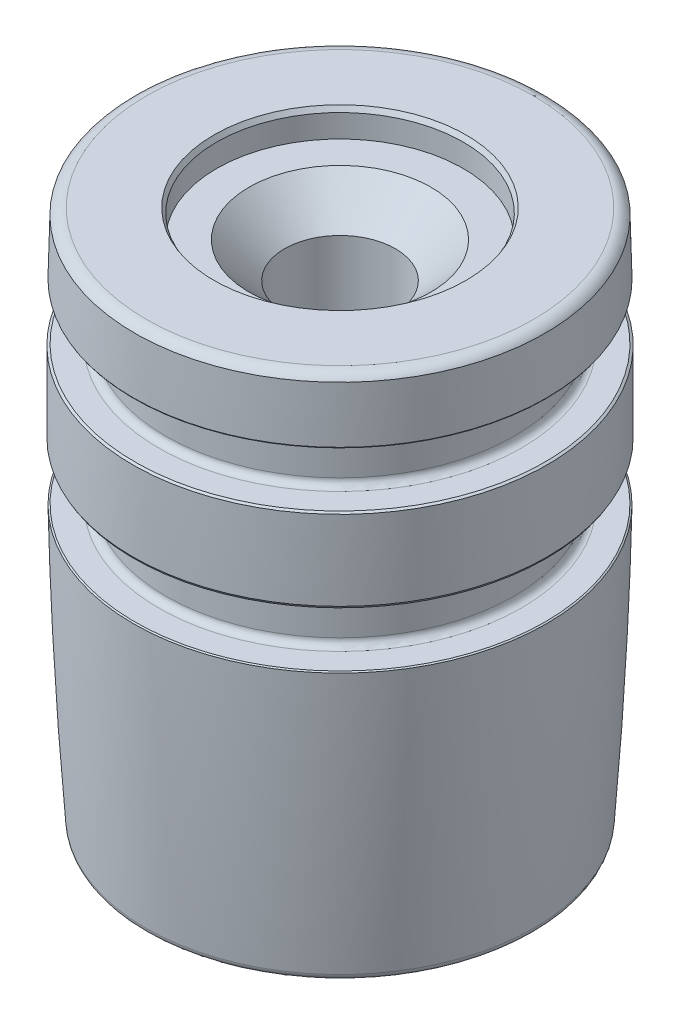
SolidWorks part; units mm, degrees
material "Delrin (POM), Black"
ref_plane "Front Plane" through (0, 0, 0) normal (0, 0, 1) x (1, 0, 0)
ref_plane "Top Plane" through (0, 0, 0) normal (0, 1, 0) x (1, 0, 0)
ref_plane "Right Plane" through (0, 0, 0) normal (1, 0, 0) x (0, 0, -1)
sketch "Sketch1" plane through (0, 0, 0) normal (0, 0, 1) x (1, 0, 0)
  line L0 (-8.9, 0) -> (-14.975, 0)
  line L1 (-14.975, 0) -> (-14.975, -4.5)
  line L2 (-14.975, -4.5) -> (-12.575, -4.5)
  line L3 (-12.575, -4.5) -> (-12.575, -8.5)
  line L4 (-12.575, -8.5) -> (-14.975, -8.5)
  line L5 (-14.975, -8.5) -> (-14.975, -14.5)
  line L6 (-14.975, -14.5) -> (-12.575, -14.5)
  line L7 (-12.575, -14.5) -> (-12.575, -18.5)
  line L8 (-12.575, -18.5) -> (-14.975, -18.5)
  line L9 (-14.975, -18.5) -> (-14.975, -38.5)
  line L10 (-14.975, -38.5) -> (-9.535, -38.5)
  line L11 (-9.535, -38.5) -> (-9.535, -22.5)
  line L12 (-9.535, -22.5) -> (-4, -22.5)
  line L13 (-4, -22.5) -> (-4, -4.5657)
  line L14 (-6.5657, -2) -> (-8.9, -2)
  line L15 (-8.9, -2) -> (-8.9, 0)
  line L16 (0, 0) -> (0, -38.5) construction
  line L17 (-3.9687, -30.5) -> (3.9688, -30.5) construction
  line L18 (-6.5657, -2) -> (-4, -4.5657)
  line L19 (-5.7071, -3.7071) -> (-4.2929, -2.2929) construction
  circle A0 centre (-5, -3) radius 1 construction
  circle A1 centre (-14.075, -6.6315) radius 1.5 construction
  point P19 (0, -30.5)
  point P26 (-5.2828, -3.2828)
  point P28 (-15.575, -6.6315)
  point P29 (-14.075, -6.6315)
  dimension "D11" = 2
  dimension "D17" = 3
  dimension "D1" = 19.07
  dimension "D2" = 16
  dimension "D3" = 29.95
  dimension "D4" = 8
  dimension "D5" = 7.9375
  dimension "D6" = 8
  dimension "D7" = 17.8
  dimension "D8" = 2
  dimension "D9" = 2.4
  dimension "D10" = 4
  dimension "D12" = 0.6
  dimension "D13" = 45
  dimension "D14" = 6
  dimension "D15" = 2.5
  dimension "D16" = 4
  dimension "D18" = 0.6
revolve "Revolve1" add sketch "Sketch1" angle 360 about L16
fillet "Fillet1" radius 1 2 edges at (-14.975, 0, 0) (-14.975, -38.5, 0)
chamfer "Chamfer1" distance 0.2 angle 60 1 edges at (-8.9, 0, 0)
chamfer "Chamfer2" distance 0.1 angle 60 4 edges at (-14.975, -18.5, 0) (-14.975, -14.5, 0) (-14.975, -8.5, 0) (-14.975, -4.5, 0)
fillet "Fillet2" radius 0.5 4 edges at (-12.575, -14.5, 0) (-12.575, -18.5, 0) (-12.575, -4.5, 0) (-12.575, -8.5, 0)
chamfer "Chamfer3" distance 0.4 angle 60 2 edges at (-4, -22.5, 0) (-9.535, -38.5, 0)
sketch "Sketch2" plane through (0, 0, 0) normal (0, 0, 1) x (1, 0, 0)
  line L0 (-14.975, -8.6) -> (-14.975, -14.3268) construction
  line L1 (-13.975, -38.5) -> (13.975, -38.5) construction
  line L2 (-13.7345, 18.6448) -> (-23.701, 18.6448)
  line L3 (-23.701, 18.6448) -> (-23.701, -42.8072)
  line L4 (-23.701, -42.8072) -> (-13.975, -38.5)
  line L5 (0, -0.3464) -> (0, 16.7486) construction
  line L6 (-8.9, -0.3464) -> (8.9, -0.3464) construction
  arc A0 (-13.975, -38.5) -> (-13.7345, 18.6448) centre (351.0139, -11.4634) cw
  point P3 (-14.975, -11.4634)
  dimension "D1" = 1
revolve "Cut-Revolve1" cut sketch "Sketch2" angle 360 about L5
fillet "Fillet3" radius 0.5 1 edges at (0, -38.5, -13.975)
